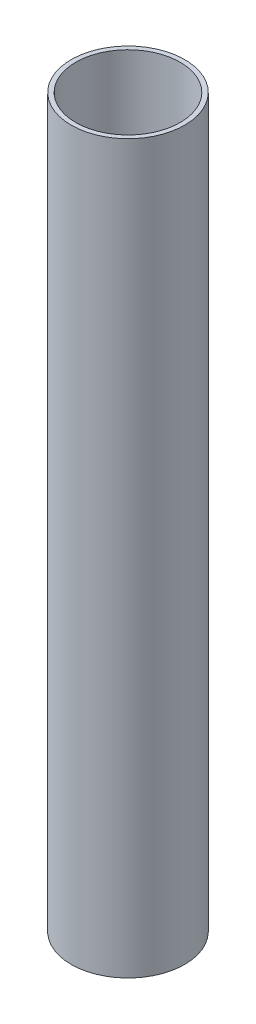
SolidWorks part; units mm, degrees
ref_plane "Front Plane" through (0, 0, 0) normal (0, 0, 1) x (1, 0, 0)
ref_plane "Top Plane" through (0, 0, 0) normal (0, 1, 0) x (1, 0, 0)
ref_plane "Right Plane" through (0, 0, 0) normal (1, 0, 0) x (0, 0, -1)
sketch "Sketch1" plane through (0, 0, 0) normal (0, 1, 0) x (1, 0, 0)
  circle A0 centre (0, 0) radius 11.5
  circle A1 centre (0, 0) radius 12.5
  dimension "D1" = 23
  dimension "D2" = 25
extrude "Boss-Extrude1" add sketch "Sketch1" along normal blind 160
